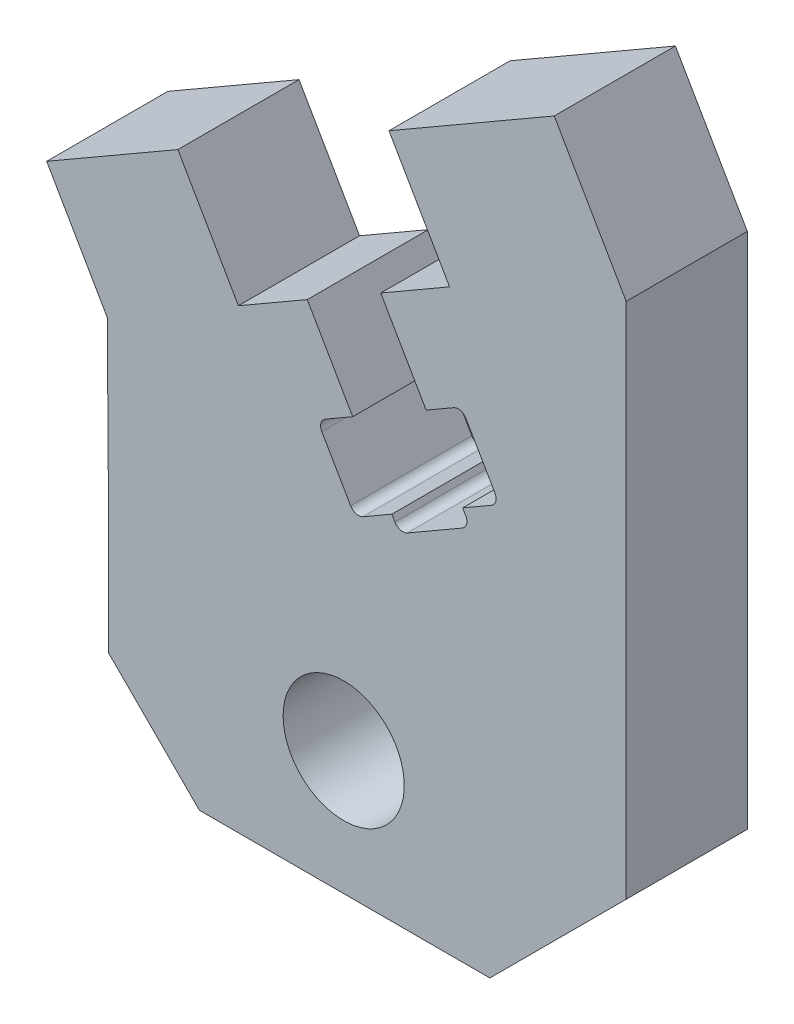
SolidWorks part; units mm, degrees
ref_plane "前视基准面" through (0, 0, 0) normal (0, 0, 1) x (1, 0, 0)
ref_plane "上视基准面" through (0, 0, 0) normal (0, 1, 0) x (1, 0, 0)
ref_plane "右视基准面" through (0, 0, 0) normal (1, 0, 0) x (0, 0, -1)
sketch "草图1" plane through (0, 0, 0) normal (0, 0, 1) x (1, 0, 0)
  line L1 (-111.6207, 100.3725) -> (-127.2092, 100.3725)
  line L3 (-127.2092, 100.3725) -> (-127.2516, 105.9422)
  line L4 (-127.2516, 105.9422) -> (-111.6207, 114.9666)
  line L6 (-111.6207, 114.9666) -> (-111.6207, 100.3725)
extrude "凸台-拉伸1" add sketch "草图1" along normal blind 4
sketch "草图3" plane through (0, 100.3725, 0) normal (0, -1, 0) x (1, 0, 0)
  line L4 (-127.2092, 0) -> (-111.6207, 0)
  line L5 (-111.6207, 0) -> (-111.6207, 4)
  line L6 (-111.6207, 4) -> (-127.2092, 4)
  line L7 (-127.2092, 4) -> (-127.2092, 0)
  line L8 (-127.2092, 0) -> (-111.6207, 0)
  line L9 (-111.6207, 0) -> (-111.6207, 4)
  line L10 (-111.6207, 4) -> (-127.2092, 4)
  line L11 (-127.2092, 4) -> (-127.2092, 0)
  dimension "D1" = 0
extrude "凸台-拉伸3" add sketch "草图3" along normal blind 2
sketch "草图4" plane through (-77.6872, 134.5582, 0) normal (-0.5, 0.866, 0) x (0.866, 0.5, 0)
  line L1 (-57.232, -4) -> (-57.232, 0) construction
  line L2 (-39.1831, -4) -> (-57.232, -4) construction
  line L3 (-39.1831, -4) -> (-39.1831, 0) construction
  line L4 (-52.232, -4) -> (-52.232, 0)
  line L5 (-39.1831, 0) -> (-57.232, 0) construction
  line L7 (-44.1831, 0) -> (-44.1831, -4)
  line L8 (-44.1831, -4) -> (-48.2075, -4)
  line L9 (-39.1831, 0) -> (-44.1831, 0)
  line L10 (-39.1831, -4) -> (-48.2075, -4)
  line L11 (-57.232, -4) -> (-57.232, 0)
  line L12 (-39.1831, -4) -> (-39.1831, 0)
  line L13 (-52.232, 0) -> (-57.232, 0)
  line L14 (-52.232, -4) -> (-57.232, -4)
  line M1 (-39.1831, 0) -> (-57.232, 0)
  line M2 (-57.232, 0) -> (-57.232, -4)
  line M3 (-57.232, -4) -> (-39.1831, -4)
  line M4 (-39.1831, -4) -> (-39.1831, 0)
  dimension "D1" = 5
  dimension "D2" = 5
sketch "草图19" plane through (0, 98.3725, 0) normal (0, -1, 0) x (1, 0, 0)
  line L4 (-127.2092, 4) -> (-127.2092, 0)
  line L5 (-127.2092, 0) -> (-111.6207, 0)
  line L6 (-111.6207, 0) -> (-111.6207, 4)
  line L7 (-111.6207, 4) -> (-127.2092, 4)
  line L8 (-127.2092, 4) -> (-127.2092, 0)
  line L9 (-127.2092, 0) -> (-111.6207, 0)
  line L10 (-111.6207, 0) -> (-111.6207, 4)
  line L11 (-111.6207, 4) -> (-127.2092, 4)
  dimension "D1" = 0
extrude "凸台-拉伸5" add sketch "草图19" along normal blind 5
extrude "凸台-拉伸6" add sketch "草图4" along normal blind 5 contours L4 M3 M1 M2 | L7 M1 M3 M4
ref_plane "基准面1" through (-41.749, -24.1038, 0) normal (0.866, 0.5, 0) x (0, 0, -1)
extrude "切除-拉伸17" cut sketch "草图22" against normal blind 150
sketch "草图22" plane through (0.8018, -4.5585, 5) normal (0, 0, 1) x (1, 0.0076, 0)
  circle A1 centre (-119.4684, 102.9285) radius 2
chamfer "倒角1" distance 3 angle 45 2 edges at (-111.6207, 93.3725, 2) (-127.2092, 93.3725, 2)
sketch "草图25" plane through (0, 0, 0) normal (0, 0, -1) x (-1, 0, 0)
  line L2 (111.6207, 96.3725) -> (111.6207, 114.9666) construction
  line L3 (111.6207, 96.3725) -> (111.6207, 114.9666)
  line L4 (114.1207, 119.2968) -> (111.6207, 114.9666) construction
  line L5 (114.1207, 119.2968) -> (111.6207, 114.9666)
  line L7 (110.1207, 114.9666) -> (110.1207, 97.8725)
  line L8 (110.1207, 114.9666) -> (112.9957, 119.9463)
  line L9 (112.9957, 119.9463) -> (114.1207, 119.2968)
  line L10 (111.6207, 96.3725) -> (110.1207, 97.8725)
extrude "凸台-拉伸7" add sketch "草图25" against normal up to surface (4 mm away) up to face at (-121.446, 97.4583, 4)
sketch "草图27" plane through (-80.1872, 138.8883, 0) normal (-0.5, 0.866, 0) x (0.866, 0.5, 0)
  line L4 (-57.232, -4) -> (-52.232, -4)
  line L5 (-52.232, -4) -> (-52.232, 0)
  line L6 (-52.232, 0) -> (-57.232, 0)
  line L7 (-57.232, 0) -> (-57.232, -4)
  line L8 (-57.232, -4) -> (-52.232, -4)
  line L9 (-52.232, -4) -> (-52.232, 0)
  line L10 (-52.232, 0) -> (-57.232, 0)
  line L11 (-57.232, 0) -> (-57.232, -4)
  line L12 (-37.884, 0) -> (-44.1831, 0)
  line L13 (-44.1831, 0) -> (-44.1831, -4)
  line L14 (-44.1831, -4) -> (-37.884, -4)
  line L15 (-37.884, -4) -> (-37.884, 0)
  line L16 (-37.884, 0) -> (-44.1831, 0)
  line L17 (-44.1831, 0) -> (-44.1831, -4)
  line L18 (-44.1831, -4) -> (-37.884, -4)
  line L19 (-37.884, -4) -> (-37.884, 0)
  dimension "D1" = 0
  dimension "D2" = 0
extrude "切除-拉伸19" cut sketch "草图27" against normal blind 1
extrude "切除-拉伸22" cut sketch "草图30" against normal blind 5
sketch "草图30" plane through (0.8018, -4.5585, 0) normal (0, 0, -1) x (-1, -0.0076, 0)
  line L1 (116.6618, 114.0055) -> (117.8953, 116.18)
  line L3 (115.7485, 114.5236) -> (116.6618, 114.0055)
  line L5 (114.4021, 112.758) -> (115.3395, 114.4107)
  line L7 (115.4718, 111.8063) -> (114.515, 112.3491)
  line L9 (115.3731, 111.6324) -> (115.4718, 111.8063)
  line L11 (117.3126, 110.1873) -> (115.486, 111.2234)
  line L13 (117.8202, 110.4742) -> (117.7216, 110.3002)
  line L15 (118.777, 109.9314) -> (117.8202, 110.4742)
  line L17 (120.1234, 111.697) -> (119.186, 110.0443)
  line L19 (119.0972, 112.624) -> (120.0105, 112.1059)
  line L21 (120.3307, 114.7985) -> (119.0972, 112.624)
  line L22 (117.8953, 116.18) -> (118.8653, 117.929)
  line L23 (118.8653, 117.929) -> (121.3308, 116.5616)
  line L24 (121.3308, 116.5616) -> (120.3307, 114.7985)
  arc A1 (115.7485, 114.5236) -> (115.3395, 114.4107) centre (115.6005, 114.2626) ccw
  arc A3 (114.4021, 112.758) -> (114.515, 112.3491) centre (114.663, 112.61) ccw
  arc A5 (115.3731, 111.6324) -> (115.486, 111.2234) centre (115.634, 111.4844) ccw
  arc A7 (117.3126, 110.1873) -> (117.7216, 110.3002) centre (117.4606, 110.4482) ccw
  arc A9 (118.777, 109.9314) -> (119.186, 110.0443) centre (118.925, 110.1924) ccw
  arc A11 (120.1234, 111.697) -> (120.0105, 112.1059) centre (119.8625, 111.845) ccw
